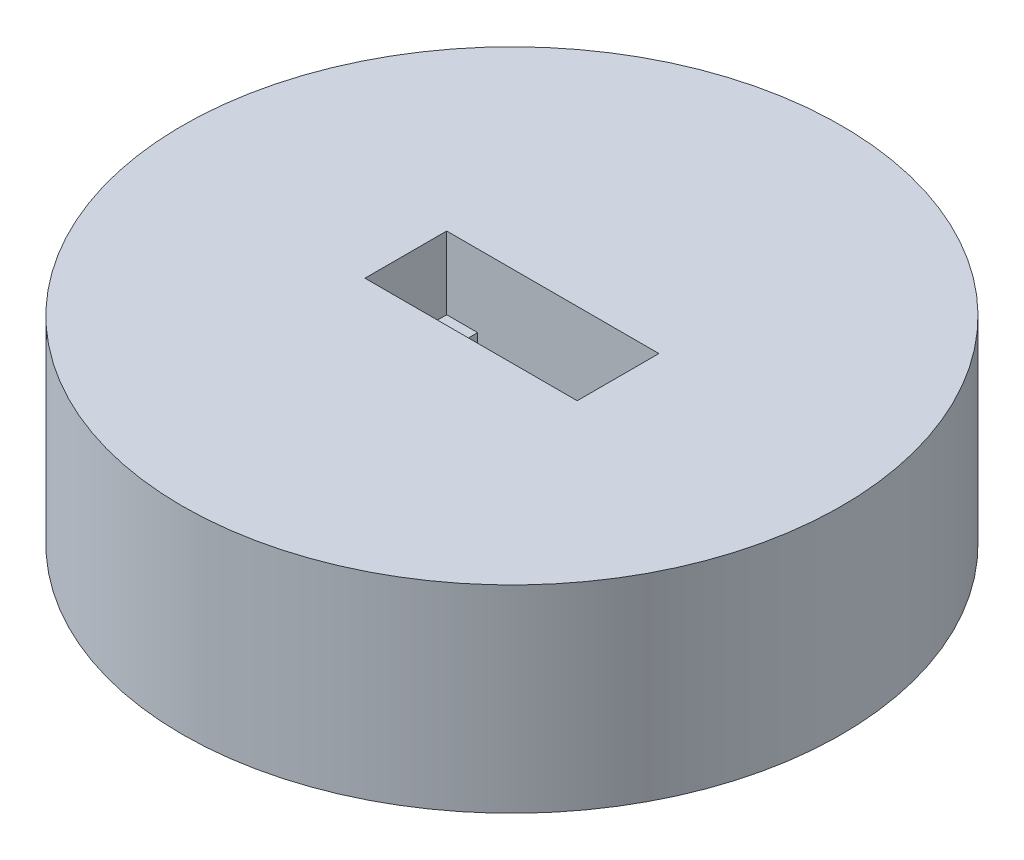
SolidWorks part; units mm, degrees
material "Custom Plastic"
ref_plane "Alzado" through (0, 0, 0) normal (0, 0, 1) x (1, 0, 0)
ref_plane "Planta" through (0, 0, 0) normal (0, 1, 0) x (1, 0, 0)
ref_plane "Vista lateral" through (0, 0, 0) normal (1, 0, 0) x (0, 0, -1)
sketch "Sketch1" plane through (0, 0, 0) normal (0, 1, 0) x (1, 0, 0)
  circle A0 centre (0, 0) radius 50
  dimension "D1" = 100
extrude "Boss-Extrude1" add sketch "Sketch1" along normal blind 30
sketch "Sketch2" plane through (0, 30, 0) normal (0, 1, 0) x (1, 0, 0)
  line L1 (11.4, 6.2) -> (-11.4, 6.2)
  line L2 (11.4, 6.2) -> (11.4, -6.2)
  line L3 (11.4, -6.2) -> (-11.4, -6.2)
  line L4 (-11.4, 6.2) -> (-11.4, -6.2)
  line L5 (11.4, 6.2) -> (-11.4, -6.2) construction
  line L6 (11.4, -6.2) -> (-11.4, 6.2) construction
  point P0 (0, 0)
  dimension "D1" = 12.4
  dimension "D2" = 22.8
extrude "Cut-Extrude1" cut sketch "Sketch2" against normal blind 27
sketch "Sketch3" plane through (0, 0, 0) normal (1, 0, 0) x (0, 0, -1)
  line L0 (50, 30) -> (-50, 30) construction
  line L1 (2, 7.5) -> (-2, 7.5)
  line L2 (2, 7.5) -> (2, 9)
  line L3 (2, 9) -> (-2, 9)
  line L4 (-2, 7.5) -> (-2, 9)
  line L5 (2, 7.5) -> (-2, 9) construction
  line L6 (2, 9) -> (-2, 7.5) construction
  point P0 (0, 8.25)
  dimension "D1" = 21
  dimension "D2" = 4
  dimension "D3" = 1.5
extrude "Cut-Extrude2" cut sketch "Sketch3" against normal through all
sketch "Sketch4" plane through (0, 30, 0) normal (0, 1, 0) x (1, 0, 0)
  line L1 (16.1, 6.2) -> (-16.1, 6.2)
  line L2 (16.1, 6.2) -> (16.1, -6.2)
  line L3 (16.1, -6.2) -> (-16.1, -6.2)
  line L4 (-16.1, 6.2) -> (-16.1, -6.2)
  line L5 (16.1, 6.2) -> (-16.1, -6.2) construction
  line L6 (16.1, -6.2) -> (-16.1, 6.2) construction
  point P1 (0, 0)
  dimension "D1" = 12.4
  dimension "D2" = 32.2
extrude "Cut-Extrude3" cut sketch "Sketch4" against normal blind 11
sketch "Sketch5" plane through (0, 30, 0) normal (0, 1, 0) x (1, 0, 0)
  line L0 (16.1, 6.2) -> (-16.1, 6.2) construction
  line L1 (19.1, 9.2) -> (-19.1, 9.2)
  line L2 (19.1, 9.2) -> (19.1, -9.2)
  line L3 (19.1, -9.2) -> (-19.1, -9.2)
  line L4 (-19.1, 9.2) -> (-19.1, -9.2)
  line L5 (19.1, 9.2) -> (-19.1, -9.2) construction
  line L6 (19.1, -9.2) -> (-19.1, 9.2) construction
  line L7 (16.1, -6.2) -> (16.1, 6.2) construction
  line L9 (29.1, 24.2) -> (-29.1, 24.2)
  line L10 (29.1, 24.2) -> (29.1, -24.2)
  line L11 (29.1, -24.2) -> (-29.1, -24.2)
  line L12 (-29.1, 24.2) -> (-29.1, -24.2)
  line L13 (29.1, 24.2) -> (-29.1, -24.2) construction
  line L14 (29.1, -24.2) -> (-29.1, 24.2) construction
  point P0 (0, 0)
  point P10 (0, 0)
  dimension "D1" = 3
  dimension "D2" = 3
  dimension "D3" = 15
  dimension "D4" = 10
extrude "Cut-Extrude6" cut sketch "Sketch5" against normal blind 25 from offset 3 offset against normal yes
sketch "Sketch6" plane through (0, 30, 0) normal (0, 1, 0) x (1, 0, 0)
  circle A0 centre (0, 0) radius 45
  circle A1 centre (0, 0) radius 50 construction
  circle A2 centre (0, 0) radius 22.1136
  dimension "D1" = 5
extrude "Cut-Extrude9" cut sketch "Sketch6" against normal blind 25 from offset 3
